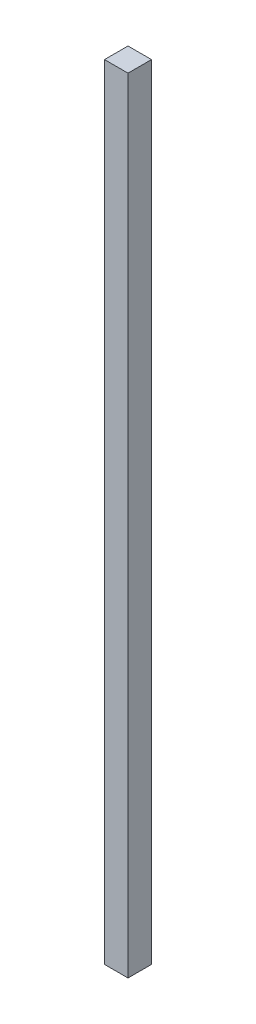
SolidWorks part; units mm, degrees
ref_plane "정면" through (0, 0, 0) normal (0, 0, 1) x (1, 0, 0)
ref_plane "윗면" through (0, 0, 0) normal (0, 1, 0) x (1, 0, 0)
ref_plane "우측면" through (0, 0, 0) normal (1, 0, 0) x (0, 0, -1)
sketch "스케치1" plane through (0, 0, 0) normal (0, 1, 0) x (1, 0, 0)
  line L1 (0, 0) -> (30, 0)
  line L2 (0, 0) -> (0, 30)
  line L3 (0, 30) -> (30, 30)
  line L4 (30, 0) -> (30, 30)
  dimension "D1" = 30
  dimension "D2" = 30
extrude "보스-돌출1" add sketch "스케치1" along normal blind 1000
